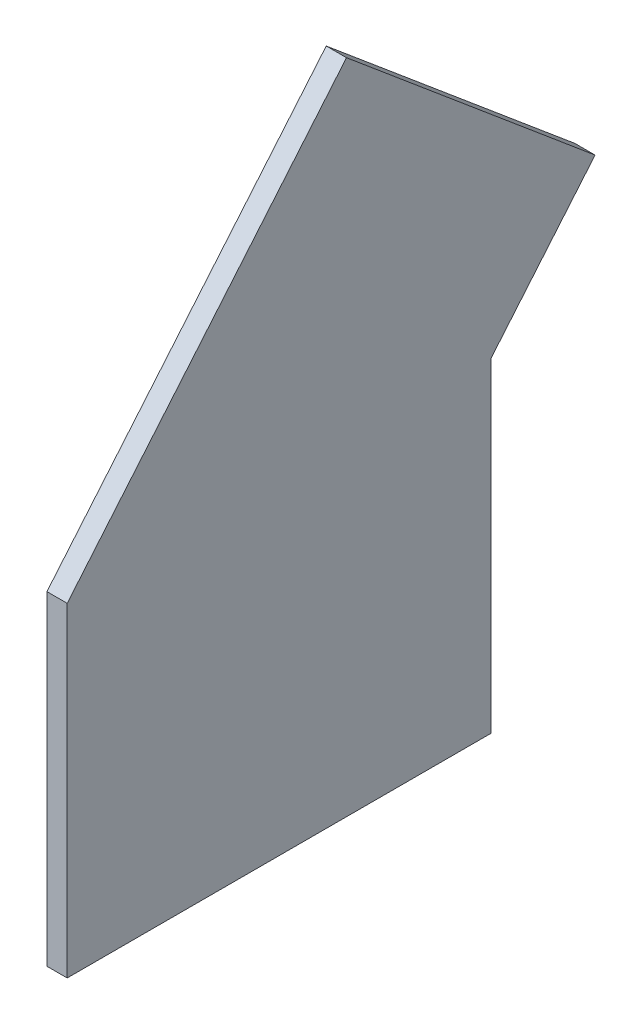
SolidWorks part; units mm, degrees
material "6061-T6 (SS)"
ref_plane "Front Plane" through (0, 0, 0) normal (0, 0, 1) x (1, 0, 0)
ref_plane "Top Plane" through (0, 0, 0) normal (0, 1, 0) x (1, 0, 0)
ref_plane "Right Plane" through (0, 0, 0) normal (1, 0, 0) x (0, 0, -1)
sketch "Sketch1" plane through (0, 0, 0) normal (1, 0, 0) x (0, 0, -1)
  line L0 (0, 0) -> (0, 50.8)
  line L2 (-22.5883, 102.9111) -> (-66.3147, 50.8)
  line L3 (-66.3147, 50.8) -> (-66.3147, 0)
  line L4 (-66.3147, 0) -> (0, 0)
  line L5 (0, 50.8) -> (16.3268, 70.2575)
  line L6 (-66.3147, 50.8) -> (74.596, 218.7308) construction
  line L7 (-22.5883, 102.9111) -> (16.3268, 70.2575)
  dimension "D1" = 50.8
  dimension "D3" = 50.8
  dimension "D4" = 25.4
extrude "Boss-Extrude1" add sketch "Sketch1" along normal blind 3.175
